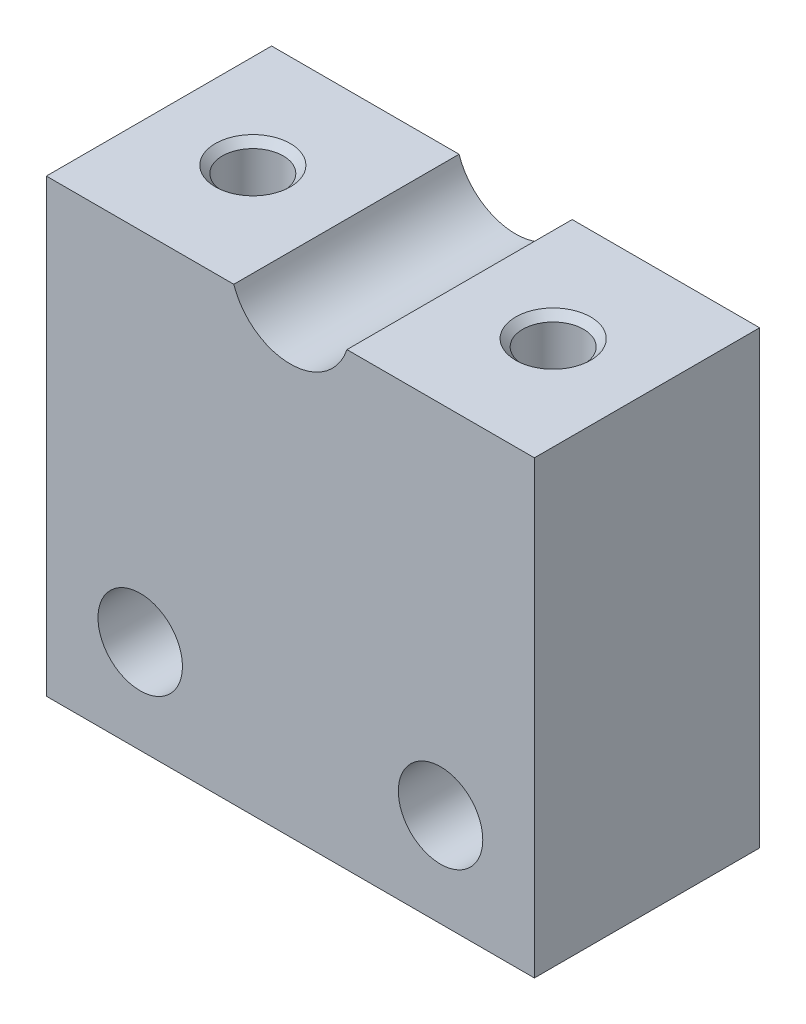
SolidWorks part; units mm, degrees
ref_plane "Front Plane" through (0, 0, 0) normal (0, 0, 1) x (1, 0, 0)
ref_plane "Top Plane" through (0, 0, 0) normal (0, 1, 0) x (1, 0, 0)
ref_plane "Right Plane" through (0, 0, 0) normal (1, 0, 0) x (0, 0, -1)
ref_plane "Plane1" through (0, 0, 6) normal (0, 0, 1) x (1, 0, 0)
sketch "Sketch1" plane through (0, 0, 6) normal (0, 0, 1) x (1, 0, 0)
  line L0 (13, 24) -> (-13, 24)
  line L1 (-13, 24) -> (-13, 0)
  line L2 (-13, 0) -> (13, 0)
  line L3 (13, 0) -> (13, 24)
extrude "Boss-Extrude1" add sketch "Sketch1" against normal blind 12
sketch "Sketch2" plane through (0, 0, -6) normal (0, 0, -1) x (-1, 0, 0)
  line L0 (3.0134, 24) -> (-3.0134, 24)
  line L1 (-13, 24) -> (13, 24) construction
  arc A0 (-3.0134, 24) -> (3.0134, 24) centre (0, 25) ccw
  dimension "D1" = 3.175
  dimension "D2" = 1
extrude "Cut-Extrude1" cut sketch "Sketch2" against normal through all
hole_wizard "M3 Clearance Hole1" positions "Sketch4" profile "Sketch3" hole size "M3" standard "ANSI Metric"
sketch "Sketch4" plane through (0, 24, 0) normal (0, 1, 0) x (1, 0, 0)
  point P0 (8, 0)
  point P1 (-8, 0)
sketch "Sketch3" plane through (8, 24, 0) normal (1, 0, 0) x (0, 0, 1)
  line L0 (0, 0) -> (0, 7)
  line L1 (0, 7) -> (1.621, 6.0641)
  line L2 (1.621, 6.0641) -> (1.621, 0)
  line L5 (1.621, 0) -> (0, 0)
  line L10 (0, 7) -> (-1.621, 6.0641) construction
  line L11 (0, -6.35) -> (0, 107.95) construction
  dimension "Hole Dia." = 3.242
  dimension "Hole Depth" = 6.0641
  dimension "Drill Angle" = 120
hole_wizard "Ø4.5 (4.5) Diameter Hole1" positions "Sketch6" profile "Sketch5" hole size "Ø4.5" standard "ANSI Metric"
sketch "Sketch6" plane through (0, 0, 6) normal (0, 0, 1) x (1, 0, 0)
  point P0 (8, 5)
  point P1 (-8, 5)
sketch "Sketch5" plane through (8, 5, 6) normal (1, 0, 0) x (0, -1, 0)
  line L0 (0, 0) -> (0, 12)
  line L1 (0, 12) -> (2.25, 12)
  line L2 (2.25, 12) -> (2.25, 0)
  line L5 (2.25, 0) -> (0, 0)
  line L11 (0, -6.35) -> (0, 107.95) construction
  dimension "Thru Hole Dia." = 4.5
  dimension "Thru Hole Depth" = 12
chamfer "Chamfer1" distance 0.379 angle 45 2 edges at (-8, 24, 1.621) (8, 24, 1.621)
